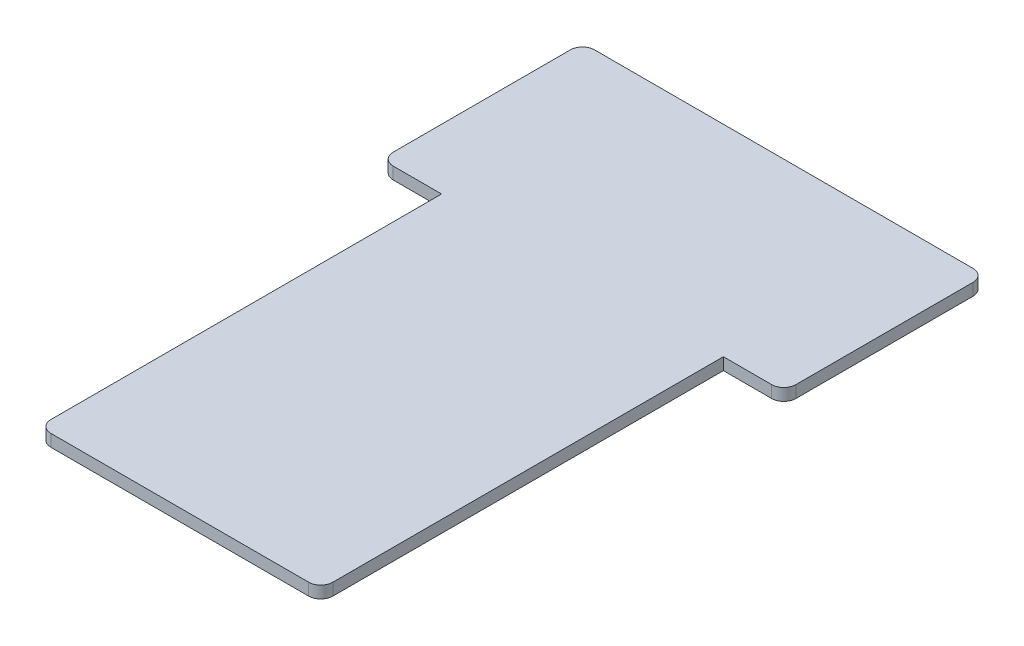
SolidWorks part; units mm, degrees
ref_plane "Alzado" through (0, 0, 0) normal (0, 0, 1) x (1, 0, 0)
ref_plane "Planta" through (0, 0, 0) normal (0, 1, 0) x (1, 0, 0)
ref_plane "Vista lateral" through (0, 0, 0) normal (1, 0, 0) x (0, 0, -1)
sketch "Croquis1" plane through (0, 0, 0) normal (0, 1, 0) x (1, 0, 0)
  line L1 (-50, -75) -> (50, -75)
  line L2 (-50, -75) -> (-50, 75)
  line L3 (-50, 75) -> (50, 75)
  line L4 (50, -75) -> (50, 75)
  line L5 (-50, -75) -> (50, 75) construction
  line L6 (-50, 75) -> (50, -75) construction
  point P0 (0, 0)
  dimension "D1" = 100
  dimension "D2" = 150
extrude "Saliente-Extruir2" add sketch "Croquis1" along normal blind 3
sketch "Croquis2" plane through (0, 3, 0) normal (0, 1, 0) x (1, 0, 0)
  line L1 (-50, -75) -> (-35, -75)
  line L2 (-50, -75) -> (-50, 25)
  line L3 (-50, 25) -> (-35, 25)
  line L4 (-35, -75) -> (-35, 25)
  line L5 (50, -75) -> (35, -75)
  line L6 (50, -75) -> (50, 25)
  line L7 (50, 25) -> (35, 25)
  line L8 (35, -75) -> (35, 25)
  dimension "D1" = 15
  dimension "D2" = 15
  dimension "D3" = 100
  dimension "D4" = 100
extrude "Cortar-Extruir1" cut sketch "Croquis2" against normal through all both and the other way through all contours L2 L1 L4 L3 | L6 L5 L8 L7
fillet "Redondeo1" radius 3 6 edges at (35, 1.5, 75) (50, 1.5, -75) (50, 1.5, -25) (-35, 1.5, 75) (-50, 1.5, -25) (-50, 1.5, -75)
